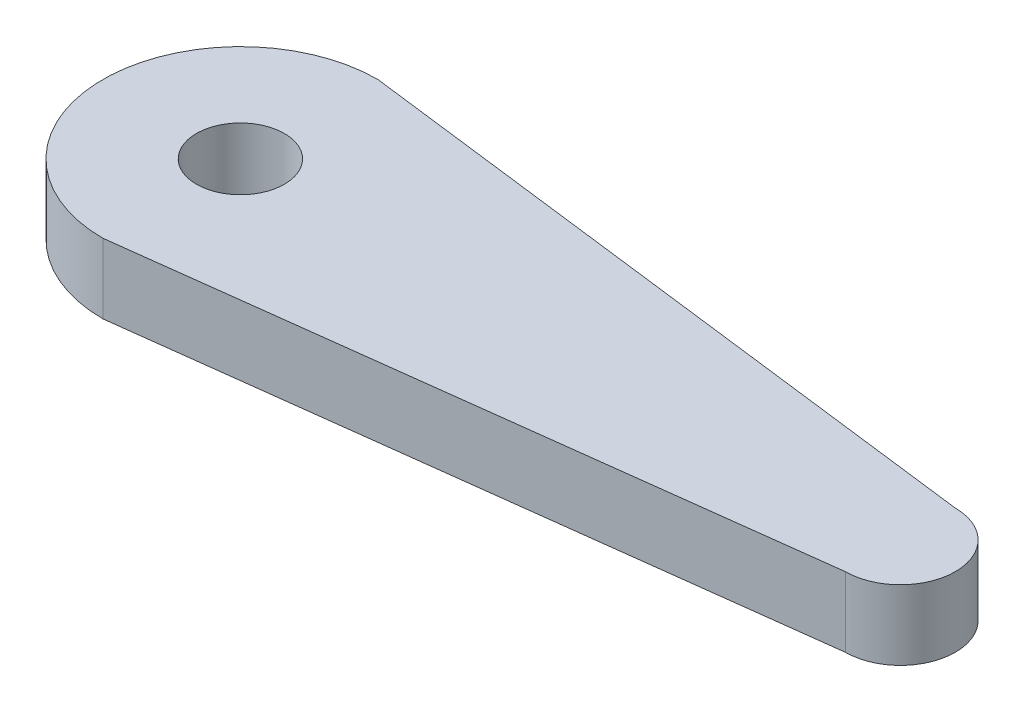
SolidWorks part; units mm, degrees
ref_plane "Front Plane" through (0, 0, 0) normal (0, 0, 1) x (1, 0, 0)
ref_plane "Top Plane" through (0, 0, 0) normal (0, 1, 0) x (1, 0, 0)
ref_plane "Right Plane" through (0, 0, 0) normal (1, 0, 0) x (0, 0, -1)
sketch "Sketch1" plane through (0, 0, 0) normal (0, 1, 0) x (1, 0, 0)
  line L0 (0, 0) -> (60, 0) construction
  line L1 (0, -12.5) -> (0, 12.5) construction
  line L2 (60, -5) -> (60, 5) construction
  line L3 (0, 12.5) -> (60, 5)
  line L4 (60, -5) -> (0, -12.5)
  arc A0 (3.0769, 12.1154) -> (3.0769, -12.1154) centre (0, 0) ccw
  arc A1 (60, -5) -> (60, 5) centre (60, 0) ccw
  circle A2 centre (0, 0) radius 4
  dimension "D1" = 25
  dimension "D2" = 10
  dimension "D4" = 8
  dimension "D3" = 60
extrude "Boss-Extrude1" add sketch "Sketch1" along normal blind 6.35 contours L4 A1 L3 A0 A2
